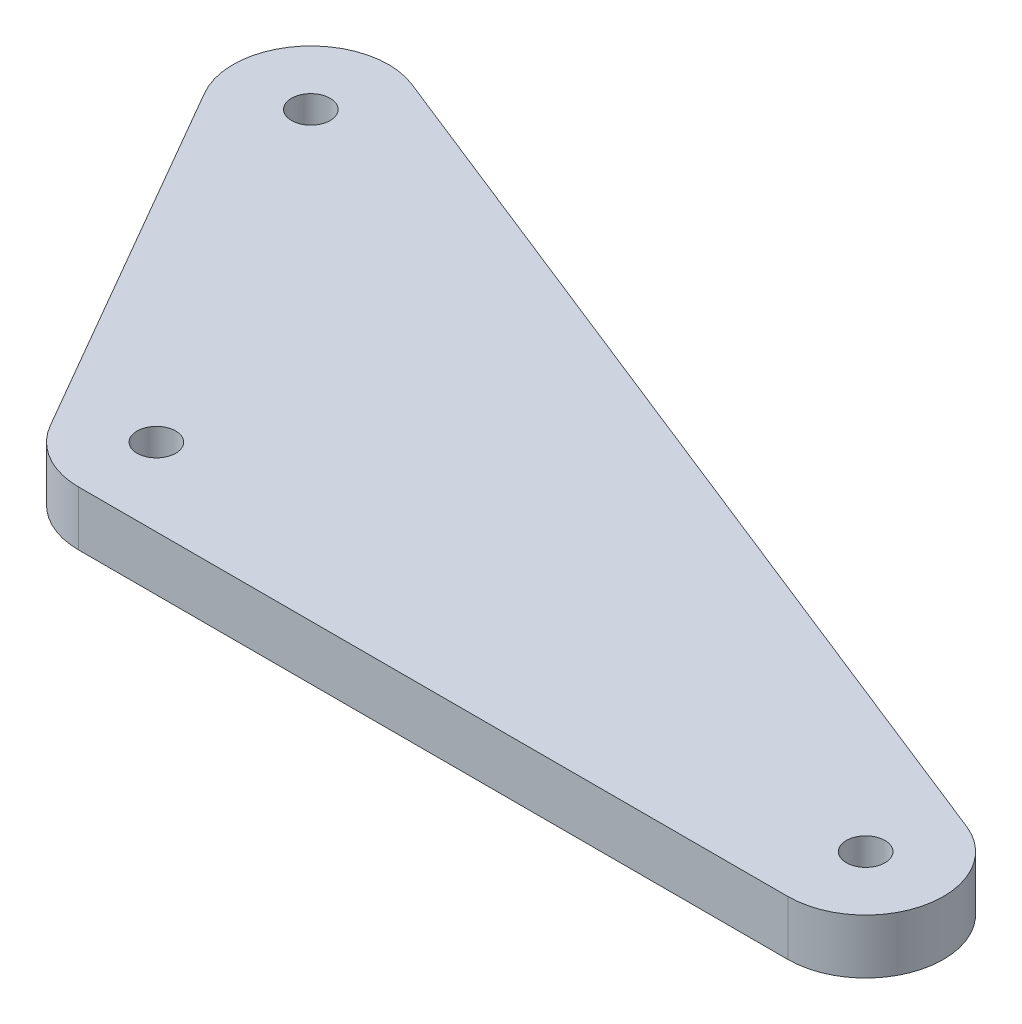
SolidWorks part; units mm, degrees
material "Acrylic (Medium-high impact)"
ref_plane "Front Plane" through (0, 0, 0) normal (0, 0, 1) x (1, 0, 0)
ref_plane "Top Plane" through (0, 0, 0) normal (0, 1, 0) x (1, 0, 0)
ref_plane "Right Plane" through (0, 0, 0) normal (1, 0, 0) x (0, 0, -1)
sketch "Sketch3" plane through (0, 0, 0) normal (0, 1, 0) x (1, 0, 0)
  line L3 (-103.7623, 50.9346) -> (3.3392, 8.4101)
  line L4 (-82.55, -9.0488) -> (0, -9.0488)
  line L5 (-114.938, 38.0002) -> (-90.3864, -4.5244)
  arc A3 (-103.7623, 50.9346) -> (-114.938, 38.0002) centre (-107.1016, 42.5245) ccw
  arc A4 (0, -9.0488) -> (3.3392, 8.4101) centre (0, 0) ccw
  arc A5 (-90.3864, -4.5244) -> (-82.55, -9.0488) centre (-82.55, 0) ccw
  dimension "D4" = 9.0488
  dimension "D5" = 9.0488
  dimension "D6" = 9.0488
  dimension "D1" = 115.2349
  dimension "D2" = 82.55
  dimension "D3" = 49.1031
extrude "Boss-Extrude1" add sketch "Sketch3" along normal blind 6.35
hole_wizard "M4 Clearance Hole1" positions "Sketch6" profile "Sketch5" hole size "M4" standard "ANSI Metric" end condition through all
sketch "Sketch6" plane through (0, 6.35, 0) normal (0, 1, 0) x (1, 0, 0)
  arc A0 (-90.3864, -4.5244) -> (-82.55, -9.0488) centre (-82.55, 0) ccw construction
  arc A1 (-103.7623, 50.9346) -> (-114.938, 38.0002) centre (-107.1016, 42.5245) ccw construction
  point P0 (-107.1016, 42.5245)
  point P2 (-82.55, 0)
  point P4 (0, 0)
sketch "Sketch5" plane through (-107.1016, 6.35, -42.5245) normal (1, 0, 0) x (0, 0, 1)
  line L0 (0, 0) -> (0, 6.35)
  line L1 (0, 6.35) -> (2.25, 6.35)
  line L2 (2.25, 6.35) -> (2.25, 0)
  line L5 (2.25, 0) -> (0, 0)
  line L11 (0, -6.35) -> (0, 107.95) construction
  dimension "Thru Hole Dia." = 4.5
  dimension "Thru Hole Depth" = 6.35
